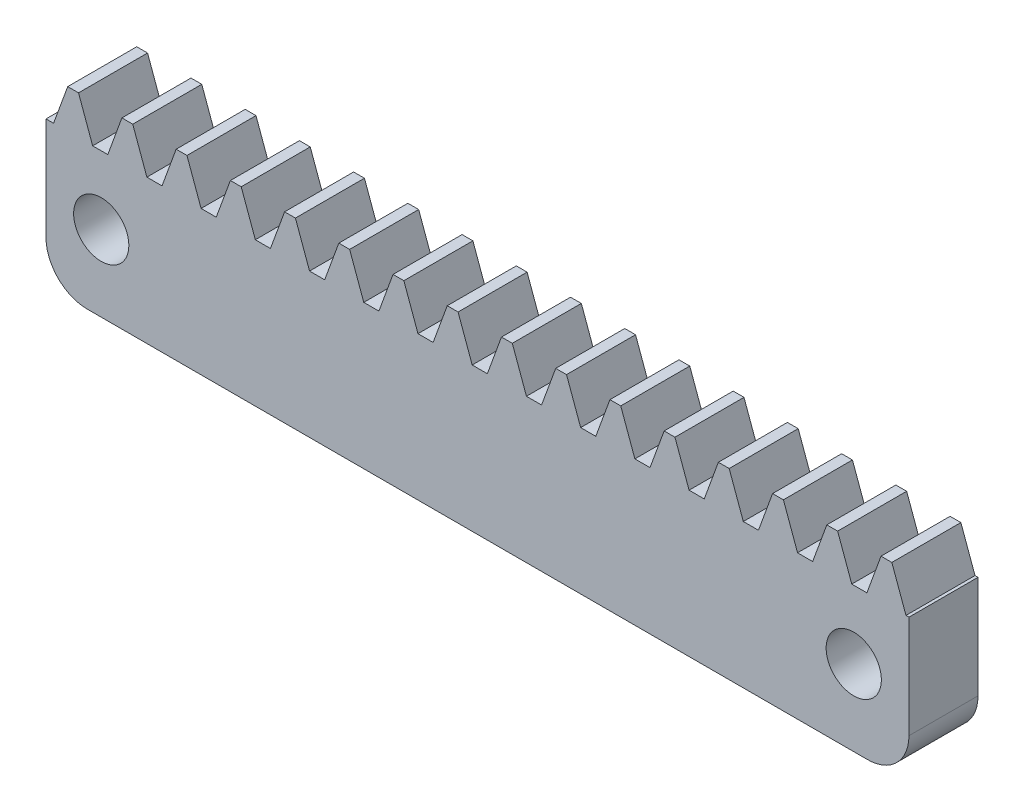
SolidWorks part; units mm, degrees
extrude "Blank" add sketch "BlankSke" against normal blind 5
sketch "BlankSke" plane through (0, 0, 0) normal (0, 0, 1) x (1, 0, 0)
  line L0 (31.25, 28.2041) -> (31.25, -22.8495) construction
  line L1 (0, 0) -> (62.5, 0)
  line L2 (0, 0) -> (0, 13.25)
  line L3 (0, 13.25) -> (62.5, 13.25)
  line L4 (62.5, 0) -> (62.5, 13.25)
  line L5 (-9.9676, 5.5) -> (69.2683, 5.5) construction
  line L6 (4, 11.8366) -> (4, 1.7559) construction
  line L7 (58.5, 11.8366) -> (58.5, 1.7559) construction
  circle A0 centre (4, 5.5) radius 2
  circle A1 centre (58.5, 5.5) radius 2
  dimension "Length" = 62.5
  dimension "Blank_height" = 13.25
  dimension "D1" = 27.25
  dimension "D2" = 31.25
  dimension "D3" = 5.5
ref_plane "Plane1" through (0, 0, 0) normal (0, 0, 1) x (1, 0, 0)
ref_plane "Plane2" through (0, 0, 0) normal (0, 1, 0) x (1, 0, 0)
ref_plane "Plane3" through (0, 0, 0) normal (1, 0, 0) x (0, 0, -1)
other "Configuration Table"
sketch "HoldingSke" plane through (0, 0, 0) normal (0, 1, 0) x (1, 0, 0)
  line L0 (0, 0) -> (0.1113, 0.7922)
  line L1 (-15, 0) -> (100, 0) construction
  line L2 (0, 0) -> (-2.1039, 2.3779)
  line L3 (0, 0) -> (-11.863, 4.5341)
  line L4 (0, 0) -> (8.2587, 2.5249)
  line L5 (0, 0) -> (-23.7986, -8.8762)
  line L6 (0, 0) -> (-10.5278, -7.1032)
  line L9 (-71.009, 38.7566) -> (-12.2782, 60.1329)
  line L10 (-76.2, 3.6279) -> (-64.2, 3.6279)
  line L11 (0, 0) -> (-5, 0)
  line L12 (-76.2, 101.6) -> (-76.155, 101.6)
  line L13 (24.9733, 27.94) -> (52.9518, 28.4284)
  line L14 (24.9733, 27.94) -> (24.9743, 27.94)
  line L15 (24.9733, 27.94) -> (100.4006, 29.5858)
  circle A0 centre (0, 0) radius 19.05
  circle A1 centre (0, 0) radius 6
  circle A2 centre (0, 0) radius 12.7
  dimension "MPH" = 12
  dimension "Diameter" = 38.1
  dimension "Num_teeth" = 17
  dimension "Pitch" = 0.8
  dimension "Show_teeth" = 998
  dimension "Thickness" = 12.7
  dimension "Ap" = 20
  dimension "Pitch_height" = 12
  dimension "Width" = 5
  dimension "Backlash" = 0.045
  dimension "Addendum_fac" = 1
  dimension "Dedendum_fac" = 1.25
  dimension "Clearance_fac" = 0.25
  dimension "Dedendum_add" = 0.001
  dimension "Length" = 62.5
  dimension "Module" = 1.25
sketch "TooCutSkeIll" plane through (0, 0, 0) normal (0, 0, 1) x (1, 0, 0)
  line L0 (-1.5597, 13.2171) -> (-0.6231, 10.6438)
  line L1 (-0.3285, 10.4375) -> (0.3285, 10.4375)
  line L2 (0.6231, 10.6438) -> (1.5597, 13.2171)
  line L3 (62.5, 13.25) -> (0, 13.25) construction
  line L4 (0, 0) -> (0, 64.897) construction
  line L5 (-13.208, 12) -> (12.954, 12) construction
  line L6 (0, 0) -> (62.5, 0) construction
  line L7 (1.1167, 12) -> (1.1167, 48.7463) construction
  line L8 (-1.1167, 12) -> (-1.1167, 48.7463) construction
  line L9 (1.6067, 13.25) -> (1.6067, 13.2754)
  line L10 (-1.6067, 13.25) -> (-1.6067, 13.2754)
  line L11 (-1.6067, 13.2754) -> (1.6067, 13.2754)
  arc A0 (0.3285, 10.4375) -> (0.6231, 10.6438) centre (0.3285, 10.751) ccw
  arc A1 (-0.6231, 10.6438) -> (-0.3285, 10.4375) centre (-0.3285, 10.751) ccw
  arc A2 (1.6067, 13.25) -> (1.5597, 13.2171) centre (1.6067, 13.2) ccw
  arc A3 (-1.5597, 13.2171) -> (-1.6067, 13.25) centre (-1.6067, 13.2) ccw
  dimension "Pitch_height" = 12
  dimension "Addendum_plus" = 1.2754
  dimension "Pressure_angle" = 20
  dimension "Gap_width" = 2.2335
  dimension "Dedendum" = 1.5625
extrude "ToothCutIll" [suppressed] cut sketch "TooCutSkeIll" against normal through all
sketch "TooCutSkeSim" plane through (0, 0, 0) normal (0, 0, 1) x (1, 0, 0)
  line L0 (0.548, 10.4375) -> (-0.548, 10.4375)
  line L1 (1.581, 13.2754) -> (0.548, 10.4375)
  line L2 (0, 17.4625) -> (0, 53.467) construction
  line L3 (1.581, 13.2754) -> (-1.581, 13.2754)
  line L6 (-1.581, 13.2754) -> (-0.548, 10.4375)
  line L9 (-1.1167, 12) -> (1.1167, 12) construction
  line L10 (0, 0) -> (62.5, 0) construction
  line L11 (1.1167, 12) -> (1.1167, 53.467) construction
  line L12 (-1.1167, 12) -> (-1.1167, 53.467) construction
  dimension "Pitch_height" = 12
  dimension "Addendum_plus" = 1.2754
  dimension "Pressure_angle" = 20
  dimension "Gap_width" = 2.2335
  dimension "Dedendum" = 1.5625
extrude "ToothCutSim" cut sketch "TooCutSkeSim" against normal through all
pattern_linear "TeethCuts" count 17 spacing 3.927 along (1, 0, 0) of "ToothCutIll", "ToothCutSim"
fillet "Fillet1" radius 3 2 edges at (62.5, 0, -2.5) (0, 0, -2.5)
equation "' \"Module@HoldingSke\" = 6.35"
equation "' \"Num_teeth@HoldingSke\" = 12"
equation "' \"Ap@HoldingSke\" =  20"
equation "' \"Ap@HoldingSke\" = 20"
equation "' \"Width@HoldingSke\" = 0.25 * 25.4"
equation "' \"Show_teeth@HoldingSke\" = 500"
equation "' \"Backlash@HoldingSke\" = 0.009 * 25.4"
equation "' \"Addendum_fac@HoldingSke\" = 1.0"
equation "' \"Dedendum_fac@HoldingSke\" = 1.25"
equation "' \"Dedendum_add@HoldingSke\" = 0.00005 * 25.4"
equation "' \"Clearance_fac@HoldingSke\" = 0.25"
equation "' \"Pitch_height@HoldingSke\" = 1 * 25.4"
equation "' \"Length@HoldingSke\" = 4.71 * 25.4"
equation "\"Pitch@HoldingSke\" = 1 / \"Module@HoldingSke\""
equation "\"MPH@HoldingSke\" = \"Dedendum_fac@HoldingSke\" / \"Pitch@HoldingSke\" + 2 * \"Dedendum_add@HoldingSke\" + 0.002 * 25.4"
equation "\"MPH@HoldingSke\" = ((sgn( \"MPH@HoldingSke\" - \"Pitch_height@HoldingSke\")+1)*( \"MPH@HoldingSke\" - \"Pitch_height@HoldingSke\"))/2 + \"Pitch_height@HoldingSke\""
equation "\"Blank_height@BlankSke\" = \"Pitch_height@HoldingSke\" + \"Addendum_fac@HoldingSke\"  / \"Pitch@HoldingSke\" "
equation "\"Length@BlankSke\" =  \"Length@HoldingSke\""
equation "\"Face_width@Blank\" = \"Width@HoldingSke\""
equation "\"Pressure_angle@TooCutSkeIll\" = \"Ap@HoldingSke\""
equation "\"Addendum_plus@TooCutSkeIll\" =  \"Addendum_fac@HoldingSke\"  / \"Pitch@HoldingSke\" + 0.001 *25.4"
equation "\"Dedendum@TooCutSkeIll\" = \"Dedendum_fac@HoldingSke\"  / \"Pitch@HoldingSke\""
equation "\"Pitch_height@TooCutSkeIll\" =  \"MPH@HoldingSke\""
equation "\"Gap_width@TooCutSkeIll\" = 3.14159265 / 2 / \"Pitch@HoldingSke\" + 6 * \"Backlash@HoldingSke\""
equation "\"Pressure_angle@TooCutSkeSim\" = \"Ap@HoldingSke\""
equation "\"Addendum_plus@TooCutSkeSim\" =  \"Addendum_fac@HoldingSke\"  / \"Pitch@HoldingSke\" + 0.001 * 25.4"
equation "\"Dedendum@TooCutSkeSim\" = \"Dedendum_fac@HoldingSke\"  / \"Pitch@HoldingSke\""
equation "\"Pitch_height@TooCutSkeSim\" =  \"MPH@HoldingSke\""
equation "\"Gap_width@TooCutSkeSim\" = 3.14159265 / 2 / \"Pitch@HoldingSke\" + 6 * \"Backlash@HoldingSke\""
equation "\"Root_fillet@TooCutSkeIll\" = \"Clearance_fac@HoldingSke\" / \"Pitch@HoldingSke\" + \"Dedendum_add@HoldingSke\""
equation "\"Break_rad@TooCutSkeIll\" = 0.02 / \"Pitch@HoldingSke\" * 2"
equation "\"Linear_pitch@TeethCuts\" = 3.14159265 / \"Pitch@HoldingSke\""
equation "\"Num_teeth@HoldingSke\" = int( ( \"Length@HoldingSke\" + 0 ) / (3.14159265 / \"Pitch@HoldingSke\")) + 0.9999  + 1"
equation " \"Num_teeth@TeethCuts\" = int( \"Show_teeth@HoldingSke\" ) + 1"
equation " \"Num_teeth@TeethCuts\" = ((sgn( \"Num_teeth@TeethCuts\" - \"Num_teeth@HoldingSke\" )-1)*( \"Num_teeth@TeethCuts\" - \"Num_teeth@HoldingSke\" ))/-2+ \"Num_teeth@HoldingSke\""
equation " \"Num_teeth@TeethCuts\" = ((sgn( \"Num_teeth@TeethCuts\" - 2.0)+1)*( \"Num_teeth@TeethCuts\" - 2.0))/2 +2.0"
